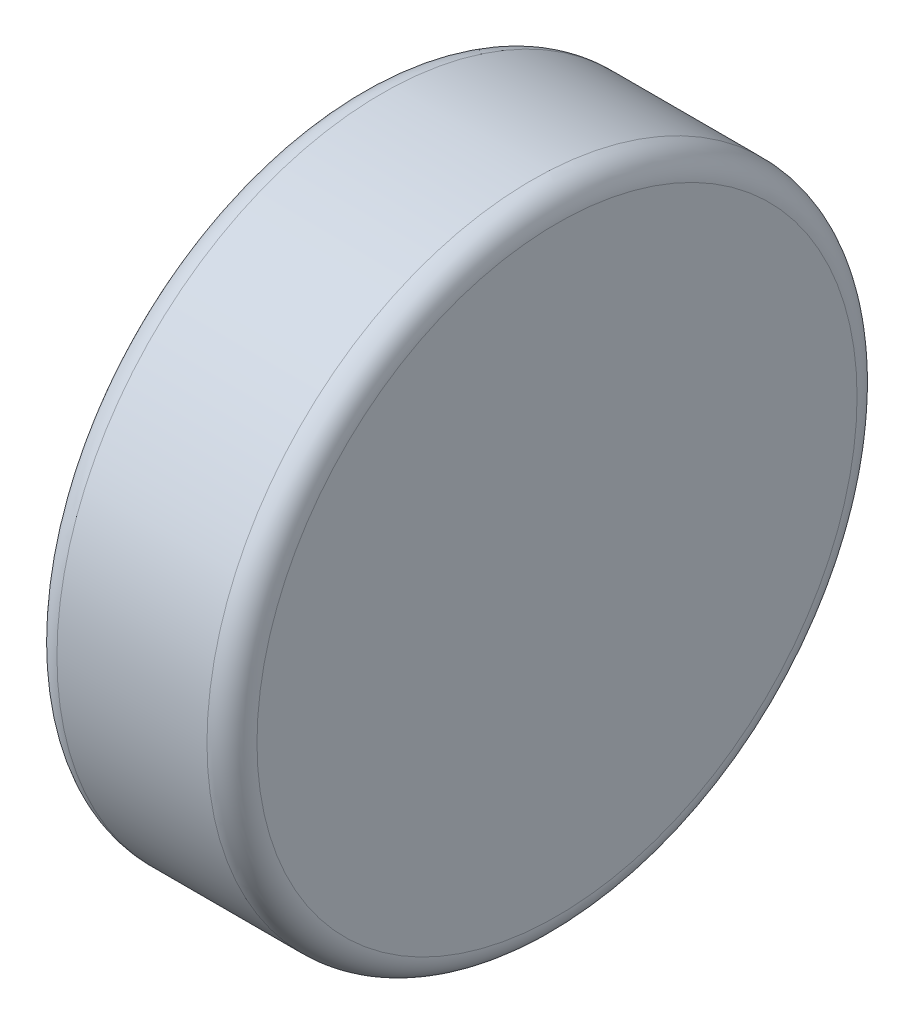
SolidWorks part; units mm, degrees
ref_plane "Front Plane" through (0, 0, 0) normal (0, 0, 1) x (1, 0, 0)
ref_plane "Top Plane" through (0, 0, 0) normal (0, 1, 0) x (1, 0, 0)
ref_plane "Right Plane" through (0, 0, 0) normal (1, 0, 0) x (0, 0, -1)
sketch "Sketch1" plane through (0, 0, 0) normal (0, 0, 1) x (1, 0, 0)
  line L1 (0, 0) -> (101.6, 0)
  line L2 (0, 0) -> (0, 165.1)
  line L3 (0, 165.1) -> (101.6, 165.1)
  line L4 (101.6, 0) -> (101.6, 165.1)
  dimension "D1" = 165.1
  dimension "D2" = 101.6
revolve "Revolve1" add sketch "Sketch1" angle 360 about L1
fillet "Fillet1" radius 12.7 2 edges at (101.6, 0, 165.1) (0, 0, 165.1)
